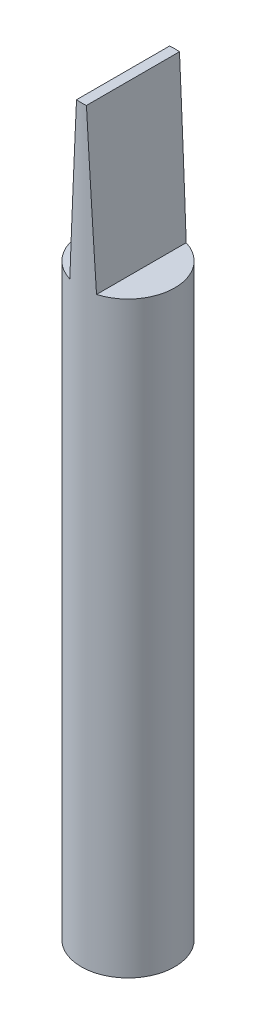
SolidWorks part; units mm, degrees
ref_plane "Front Plane" through (0, 0, 0) normal (0, 0, 1) x (1, 0, 0)
ref_plane "Top Plane" through (0, 0, 0) normal (0, 1, 0) x (1, 0, 0)
ref_plane "Right Plane" through (0, 0, 0) normal (1, 0, 0) x (0, 0, -1)
sketch "Sketch2" plane through (0, 0, 0) normal (0, 1, 0) x (1, 0, 0)
  circle A0 centre (0, 0) radius 1.75
extrude "Boss-Extrude2" add sketch "Sketch2" along normal blind 28
sketch "Sketch5" plane through (0, 28, 0) normal (0, 1, 0) x (1, 0, 0)
  line L2 (0.5, 1.6771) -> (0.5, -1.6771)
  line L3 (-0.5, -1.6771) -> (-0.5, 1.6771)
  circle A0 centre (0, 0) radius 1.75 construction
  arc A1 (-0.5, 1.6771) -> (-0.5, -1.6771) centre (0, 0) ccw
  arc A2 (0.5, 1.6771) -> (0.5, -1.6771) centre (0, 0) cw
  dimension "D1" = 1
extrude "Cut-Extrude1" cut sketch "Sketch5" against normal blind 6
sketch "Sketch7" plane through (0.5, 0, 0) normal (1, 0, 0) x (0, 0, -1)
  point P0 (-1.6771, 28)
  point P1 (-1.6771, 22)
sketch "Sketch8" plane through (-0.5, 0, 0) normal (-1, 0, 0) x (0, 0, 1)
  point P0 (1.6771, 28)
  point P1 (1.6771, 22)
  point P5 (0, 0)
ref_plane "Plane1" through (0, 0, 1.6771) normal (0, 0, -1) x (-1, 0, 0)
sketch "Sketch9" plane through (0, 0, 1.6771) normal (0, 0, -1) x (-1, 0, 0)
  line L0 (0.5, 22) -> (0.5, 28)
  line L1 (0.5, 22) -> (0.1856, 28)
  line L2 (0.5, 28) -> (-0.5, 28) construction
  line L3 (0.5, 28) -> (0.1856, 28)
  line L4 (-0.5, 22) -> (-0.5, 28)
  line L5 (-0.5, 22) -> (-0.1856, 28)
  line L6 (-0.5, 28) -> (-0.1856, 28)
extrude "Cut-Extrude2" cut sketch "Sketch9" against normal through all and the other way through all
